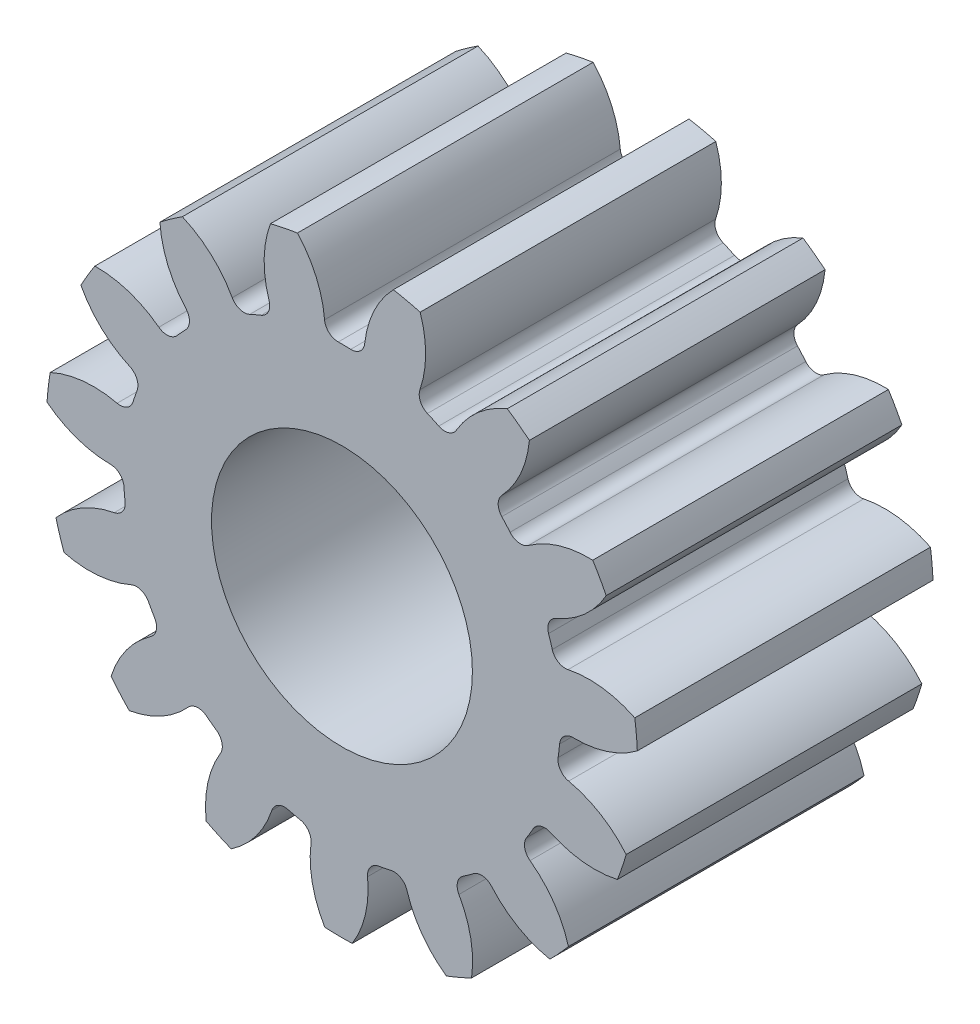
SolidWorks part; units mm, degrees
ref_plane "Front" through (0, 0, 0) normal (0, 0, 1) x (1, 0, 0)
ref_plane "Top" through (0, 0, 0) normal (0, 1, 0) x (1, 0, 0)
ref_plane "Right" through (0, 0, 0) normal (1, 0, 0) x (0, 0, -1)
sketch "Sketch3" plane through (0, 0, 0) normal (0, 0, 1) x (1, 0, 0)
  circle A0 centre (0, 0) radius 21.59
  dimension "od" = 43.18
extrude "gearBody" add sketch "Sketch3" along normal blind 25.4
sketch "Sketch2" plane through (0, 0, 0) normal (0, 0, 1) x (1, 0, 0)
  line L0 (0, 0) -> (17.0393, 7.0579) construction
  line L1 (22.0105, -8.0941) -> (0, 0) construction
  line L2 (0, 0) -> (36.3143, 0) construction
  line L3 (19.0486, -0.229) -> (18.5878, -4.1711) construction
  line L5 (18.8182, -2.2) -> (0, 0) construction
  line L7 (0, 0) -> (18.4432, 0) construction
  arc A0 (18.4395, -0.3701) -> (18.0276, -3.8932) centre (0, 0) ccw construction
  arc A1 (21.5666, 1.0048) -> (20.7532, -5.9524) centre (0, 0) ccw construction
  arc A2 (19.0486, -0.229) -> (18.5878, -4.1711) centre (0, 0) ccw construction
  arc A3 (15.7838, -2.3046) -> (15.8898, -1.3984) centre (0, 0) ccw
  arc A4 (22.0105, -8.0941) -> (16.5506, -3.4102) centre (14.9518, -10.798) ccw
  arc A5 (22.0105, -8.0941) -> (23.2839, 2.7987) centre (0, 0) ccw
  arc A6 (23.2839, 2.7987) -> (16.8909, -0.4995) centre (17.0393, 7.0579) cw
  arc A7 (15.8898, -1.3984) -> (16.8909, -0.4995) centre (16.8715, -1.4848) cw
  arc A8 (16.5506, -3.4102) -> (15.7838, -2.3046) centre (16.759, -2.4469) cw
  point P6 (23.2839, 2.7987)
  point P22 (22.0105, -8.0941)
  dimension "baseDia" = 36.8864
  dimension "od" = 43.18
  dimension "pd" = 38.1
  dimension "rd" = 31.9024
  dimension "rFillet" = 0.9855
  dimension "pointX" = 23.2839
  dimension "pointY" = 2.7987
  dimension "CTT" = 3.9421
  dimension "flankCenterAngle" = 22.5
extrude "toothCut" cut sketch "Sketch2" along normal through all
pattern_circular "CirPattern1" count 15 over 360 about axis through (0, 0, 0) along (0, 0, 1) of "toothCut"
sketch "hub1Dia" plane through (0, 0, 0) normal (0, 0, -1) x (-1, 0, 0)
  circle A0 centre (0, 0) radius 12.7
  dimension "hub1Dia" = 25.4
sketch "hub2Dia" plane through (0, 0, 25.4) normal (0, 0, 1) x (1, 0, 0)
  circle A0 centre (0, 0) radius 12.7
  dimension "hub2dia" = 25.4
sketch "boreDia" plane through (0, 0, 0) normal (0, 0, 1) x (1, 0, 0)
  circle A0 centre (0, 0) radius 9.525
  dimension "boreDia" = 19.05
extrude "bore" cut sketch "boreDia" against normal mid plane 25400
sketch "Sketch4" plane through (0, 0, 0) normal (1, 0, 0) x (0, 0, -1)
  line L0 (-3.81, 26.192) -> (-3.81, -31.8704)
  line L1 (-3.81, 26.192) -> (8.9209, 23.4815)
  line L2 (8.9209, 23.4815) -> (6.0962, -32.4684)
  line L3 (6.0962, -32.4684) -> (-3.81, -31.8704)
  dimension "D1" = 3.81
extrude "Cut-Extrude1" cut sketch "Sketch4" against normal through all both and the other way through all
